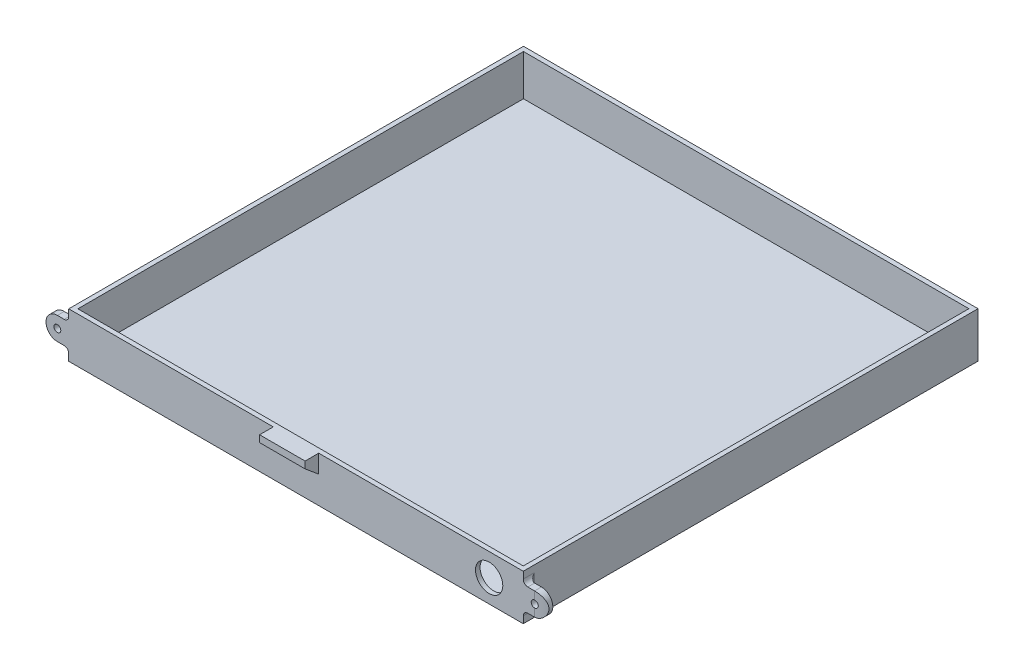
SolidWorks part; units mm, degrees
ref_plane "Front Plane" through (0, 0, 0) normal (0, 0, 1) x (1, 0, 0)
ref_plane "Top Plane" through (0, 0, 0) normal (0, 1, 0) x (1, 0, 0)
ref_plane "Right Plane" through (0, 0, 0) normal (1, 0, 0) x (0, 0, -1)
sketch "Sketch1" plane through (0, 0, 0) normal (0, 1, 0) x (1, 0, 0)
  line L1 (99.95, -100) -> (-99.95, -100)
  line L2 (99.95, -100) -> (99.95, 100)
  line L3 (99.95, 100) -> (-99.95, 100)
  line L4 (-99.95, -100) -> (-99.95, 100)
  line L5 (99.95, -100) -> (-99.95, 100) construction
  line L6 (99.95, 100) -> (-99.95, -100) construction
  point P0 (0, 0)
  dimension "D1" = 199.9
  dimension "D2" = 200
extrude "Boss-Extrude1" add sketch "Sketch1" along normal blind 20
shell "Shell1" thickness 2
sketch "Sketch2" plane through (0, 0, 100) normal (0, 0, 1) x (1, 0, 0)
  line L0 (-99.95, 20) -> (99.95, 20) construction
  line L1 (99.95, 20) -> (99.95, 0) construction
  circle A0 centre (84.95, 10) radius 6
  dimension "D1" = 12
  dimension "D2" = 10
  dimension "D3" = 15
extrude "Cut-Extrude1" cut sketch "Sketch2" against normal blind 20
sketch "Sketch3" plane through (0, 20, 0) normal (0, 1, 0) x (1, 0, 0)
  line L0 (-97.95, -98) -> (97.95, -98) construction
  line L1 (10, -106) -> (-10, -106)
  line L2 (10, -106) -> (10, -98)
  line L3 (10, -98) -> (-10, -98)
  line L4 (-10, -106) -> (-10, -98)
  line L5 (10, -106) -> (-10, -98) construction
  line L6 (10, -98) -> (-10, -106) construction
  line L7 (0, 0) -> (0, -50000) construction
  point P0 (0, -102)
  point P10 (0, 0)
  dimension "D1" = 8
  dimension "D2" = 20
extrude "Boss-Extrude2" add sketch "Sketch3" against normal blind 3
sketch "Sketch5" plane through (-10, 0, 0) normal (-1, 0, 0) x (0, 0, 1)
  line L0 (106, 17) -> (100, 12)
  line L1 (100, 20) -> (100, 0) construction
  line L2 (100, 17) -> (106, 17) construction
  dimension "D1" = 5
rib "Rib1" sketch "Sketch5" sketch "Sketch5" thickness 2 extrusion direction parallel to sketch draft on no parameters "D1"=2
mirror "Mirror1" about plane through (0, 0, 0) normal (1, 0, 0) of "Rib1"
sketch "Sketch6" plane through (0, 0, 100) normal (0, 0, 1) x (1, 0, 0)
  line L0 (-99.95, 10) -> (49900.05, 10) construction
  line L1 (-99.95, 20) -> (-99.95, 0) construction
  line L2 (-104.95, 15) -> (-99.95, 15)
  line L3 (-99.95, 15) -> (-99.95, 5)
  line L4 (-99.95, 5) -> (-104.95, 5)
  line L5 (0, 0) -> (0, 50000) construction
  line L6 (104.95, 15) -> (99.95, 15)
  line L7 (99.95, 15) -> (99.95, 5)
  line L8 (99.95, 5) -> (104.95, 5)
  circle A0 centre (-104.95, 10) radius 1.5
  arc A1 (-104.95, 15) -> (-104.95, 5) centre (-104.95, 10) ccw
  circle A2 centre (104.95, 10) radius 1.5
  arc A3 (104.95, 15) -> (104.95, 5) centre (104.95, 10) cw
  point P4 (-99.95, 10)
  dimension "D1" = 10
  dimension "D2" = 3
  dimension "D3" = 5
extrude "Boss-Extrude3" add sketch "Sketch6" against normal blind 3
sketch "Sketch7" plane through (0, 15, 0) normal (0, 1, 0) x (1, 0, 0)
  line L0 (109.95, -100) -> (109.95, -97) construction
  line L1 (104.95, -100) -> (109.95, -100) construction
  line L2 (109.95, -100) -> (109.95, -98.6889)
  line L3 (104.95, -100) -> (109.95, -100)
  arc A0 (105, -100) -> (115, -90) centre (105, -90) ccw construction
  arc A1 (105, -100) -> (109.95, -98.6889) centre (105, -90) ccw
extrude "Cut-Extrude2" cut sketch "Sketch7" against normal through all contours A1 L3 L2
fillet "Fillet1" radius 2 6 edges at (99.95, 5, 98.5) (99.95, 15, 98.5) (99.95, 10, 97) (-99.95, 10, 97) (-99.95, 5, 98.5) (-99.95, 15, 98.5)
